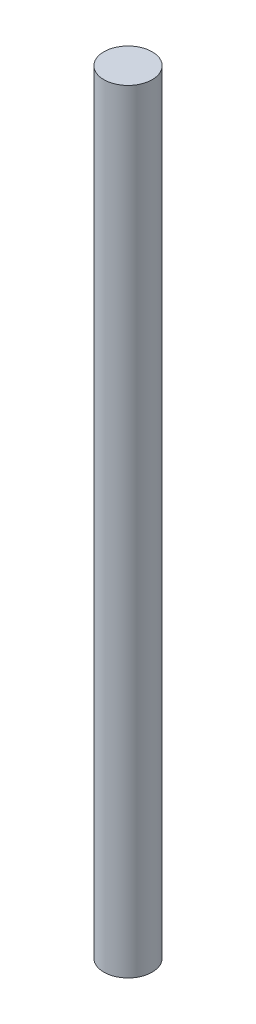
SolidWorks part; units mm, degrees
ref_plane "Front Plane" through (0, 0, 0) normal (0, 0, 1) x (1, 0, 0)
ref_plane "Top Plane" through (0, 0, 0) normal (0, 1, 0) x (1, 0, 0)
ref_plane "Right Plane" through (0, 0, 0) normal (1, 0, 0) x (0, 0, -1)
sketch "Sketch1" plane through (0, 0, 0) normal (0, 1, 0) x (1, 0, 0)
  circle A0 centre (0, 0) radius 76.2
  dimension "D1" = 152.4
extrude "Boss-Extrude1" add sketch "Sketch1" along normal blind 2438.4
